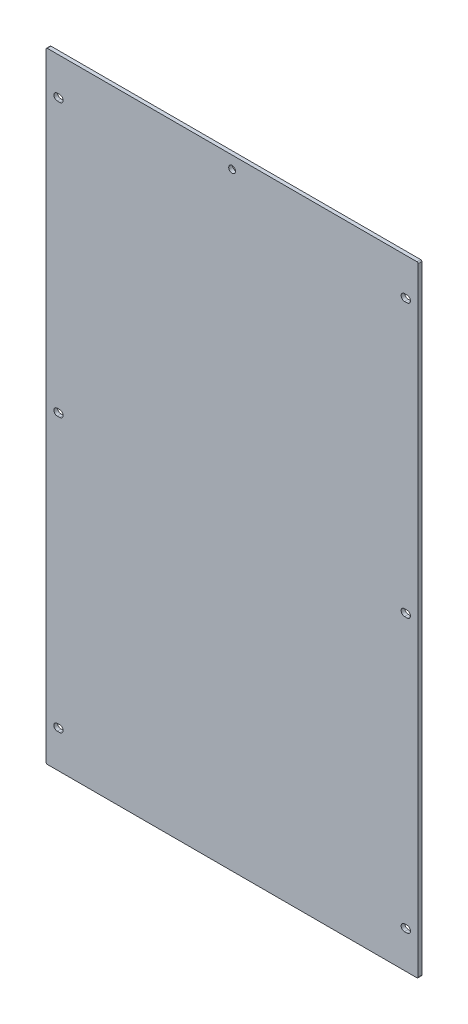
SolidWorks part; units mm, degrees
ref_plane "Front Plane" through (0, 0, 0) normal (0, 0, 1) x (1, 0, 0)
ref_plane "Top Plane" through (0, 0, 0) normal (0, 1, 0) x (1, 0, 0)
ref_plane "Right Plane" through (0, 0, 0) normal (1, 0, 0) x (0, 0, -1)
sketch "Sketch1" plane through (0, 0, 0) normal (0, 0, 1) x (1, 0, 0)
  line L1 (150, -250) -> (-150, -250)
  line L2 (150, -250) -> (150, 250)
  line L3 (150, 250) -> (-150, 250)
  line L4 (-150, -250) -> (-150, 250)
  line L5 (150, -250) -> (-150, 250) construction
  line L6 (150, 250) -> (-150, -250) construction
  point P0 (0, 0)
  dimension "D1" = 300
  dimension "D2" = 500
extrude "Boss-Extrude1" add sketch "Sketch1" along normal blind 3
sketch "Sketch2" plane through (0, 0, 3) normal (0, 0, 1) x (1, 0, 0)
  line L0 (0, 250) -> (0, -250) construction
  line L1 (150, 250) -> (-150, 250) construction
  line L2 (-150, -250) -> (150, -250) construction
  line L3 (-140, 250) -> (-140, -250) construction
  line L4 (-150, 250) -> (-150, -250) construction
  line L5 (-141, -220) -> (-139, -220) construction
  line L6 (-141, -217.25) -> (-139, -217.25)
  line L7 (-141, -222.75) -> (-139, -222.75)
  line L8 (-141, 220) -> (-139, 220) construction
  line L9 (-141, 222.75) -> (-139, 222.75)
  line L10 (-141, 217.25) -> (-139, 217.25)
  line L11 (-141, 0) -> (-139, 0) construction
  line L12 (-141, 2.75) -> (-139, 2.75)
  line L13 (-141, -2.75) -> (-139, -2.75)
  arc A0 (-141, -217.25) -> (-141, -222.75) centre (-141, -220) ccw
  arc A1 (-139, -222.75) -> (-139, -217.25) centre (-139, -220) ccw
  arc A2 (-141, 222.75) -> (-141, 217.25) centre (-141, 220) ccw
  arc A3 (-139, 217.25) -> (-139, 222.75) centre (-139, 220) ccw
  arc A4 (-141, 2.75) -> (-141, -2.75) centre (-141, 0) ccw
  arc A5 (-139, -2.75) -> (-139, 2.75) centre (-139, 0) ccw
  circle A6 centre (0, 240) radius 2.75
  point P12 (-140, -220)
  point P17 (-140, 220)
  point P24 (-140, 0)
  dimension "D3" = 2.75
  dimension "D6" = 2.75
  dimension "D8" = 440
  dimension "D10" = 2.75
  dimension "D12" = 5.5
  dimension "D13" = 10
  dimension "D1" = 10
  dimension "D2" = 2
  dimension "D4" = 30
  dimension "D5" = 2
  dimension "D7" = 30
  dimension "D9" = 220
  dimension "D11" = 2
extrude "Cut-Extrude1" cut sketch "Sketch2" against normal blind 10
mirror "Mirror1" about plane through (0, 0, 0) normal (1, 0, 0) of "Cut-Extrude1"
fillet "Fillet1" radius 1 4 edges at (-150, 250, 1.5) (150, -250, 1.5) (-150, -250, 1.5) (150, 250, 1.5)
